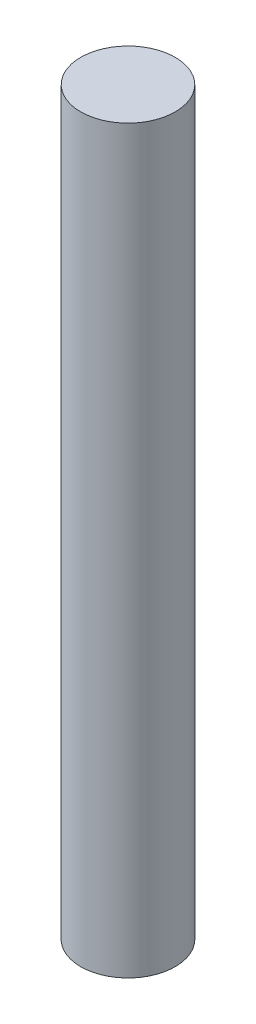
SolidWorks part; units mm, degrees
ref_plane "Front Plane" through (0, 0, 0) normal (0, 0, 1) x (1, 0, 0)
ref_plane "Top Plane" through (0, 0, 0) normal (0, 1, 0) x (1, 0, 0)
ref_plane "Right Plane" through (0, 0, 0) normal (1, 0, 0) x (0, 0, -1)
sketch "Sketch1" plane through (0, 0, 0) normal (0, 1, 0) x (1, 0, 0)
  circle A0 centre (0, 0) radius 6
  dimension "D1" = 12
extrude "Boss-Extrude1" add sketch "Sketch1" along normal blind 94
